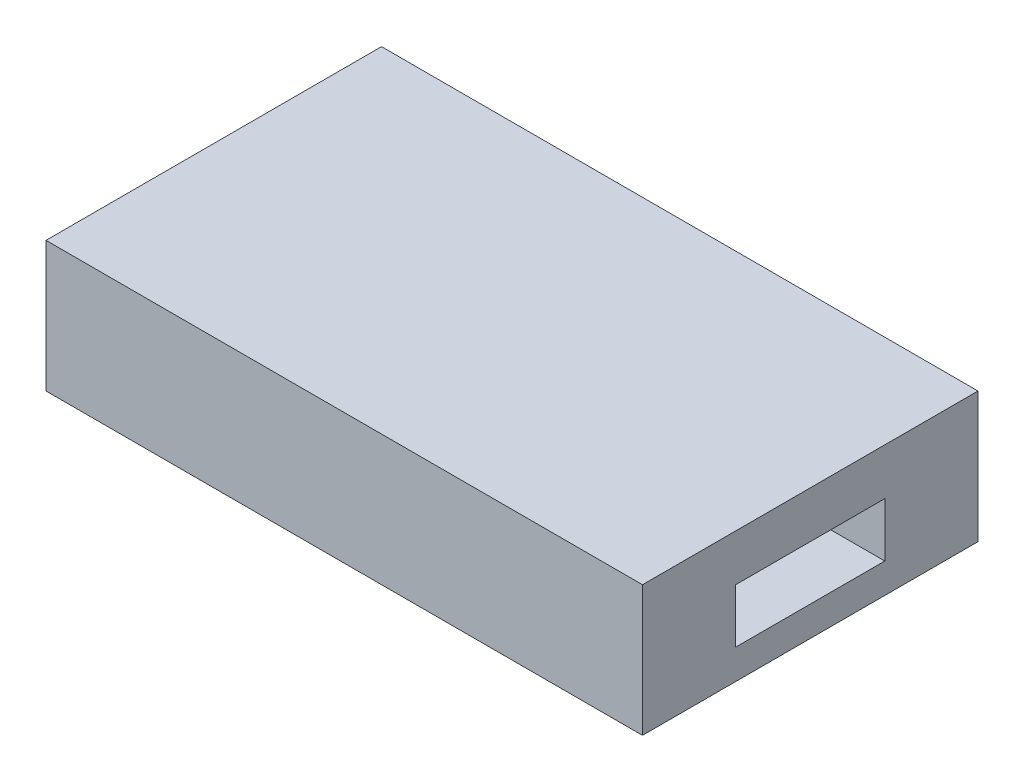
SolidWorks part; units mm, degrees
ref_plane "Front Plane" through (0, 0, 0) normal (0, 0, 1) x (1, 0, 0)
ref_plane "Top Plane" through (0, 0, 0) normal (0, 1, 0) x (1, 0, 0)
ref_plane "Right Plane" through (0, 0, 0) normal (1, 0, 0) x (0, 0, -1)
sketch "Sketch1" plane through (0, 0, 0) normal (0, 1, 0) x (1, 0, 0)
  line L1 (0, 0) -> (32, 0)
  line L2 (0, 0) -> (0, 18)
  line L3 (0, 18) -> (32, 18)
  line L4 (32, 0) -> (32, 18)
  dimension "D1" = 18
  dimension "D2" = 32
extrude "Boss-Extrude1" add sketch "Sketch1" along normal blind 7
sketch "Sketch2" plane through (32, 0, 0) normal (1, 0, 0) x (0, 0, -1)
  line L1 (5, 1.6) -> (13, 1.6)
  line L2 (5, 1.6) -> (5, 4.5)
  line L3 (5, 4.5) -> (13, 4.5)
  line L4 (13, 1.6) -> (13, 4.5)
  line L5 (0, 0) -> (18, 0) construction
  point P4 (5.0287, 0.619)
  point P5 (9, 0)
  point P8 (9, 1.6)
  dimension "D1" = 8
  dimension "D2" = 2.9
  dimension "D3" = 1.6
extrude "Cut-Extrude1" cut sketch "Sketch2" against normal blind 5
